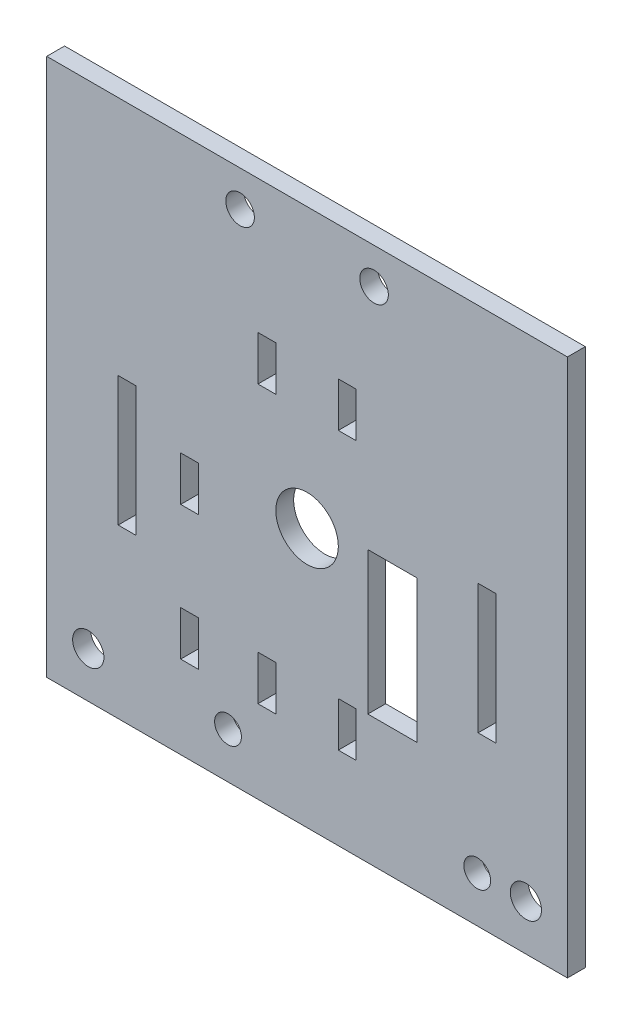
SolidWorks part; units mm, degrees
ref_plane "Front Plane" through (0, 0, 0) normal (0, 0, 1) x (1, 0, 0)
ref_plane "Top Plane" through (0, 0, 0) normal (0, 1, 0) x (1, 0, 0)
ref_plane "Right Plane" through (0, 0, 0) normal (1, 0, 0) x (0, 0, -1)
sketch "Sketch1" plane through (0, 0, 0) normal (0, 0, 1) x (1, 0, 0)
  line L0 (0, 116.93) -> (0, 0) construction
  line L1 (-25.65, 0) -> (25.65, 0)
  line L2 (-26.65, 0) -> (-26.65, 116.93) construction
  line L3 (-26.65, 116.93) -> (26.65, 116.93) construction
  line L4 (26.65, 0) -> (26.65, 116.93) construction
  line L5 (26.65, 128.7773) -> (26.65, 123.7261)
  line L6 (3.5, 106.25) -> (5.5, 106.25)
  line L7 (3.5, 106.25) -> (3.5, 101.25)
  line L8 (3.5, 101.25) -> (5.5, 101.25)
  line L9 (5.5, 106.25) -> (5.5, 101.25)
  line L10 (6.8, 91.35) -> (12.3, 91.35)
  line L11 (6.8, 91.35) -> (6.8, 75.4)
  line L12 (6.8, 75.4) -> (12.3, 75.4)
  line L13 (12.3, 91.35) -> (12.3, 75.4)
  line L14 (19.15, 94.25) -> (21.15, 94.25)
  line L15 (19.15, 94.25) -> (19.15, 79.75)
  line L16 (19.15, 79.75) -> (21.15, 79.75)
  line L17 (21.15, 94.25) -> (21.15, 79.75)
  line L18 (3.5, 75.25) -> (5.5, 75.25)
  line L19 (3.5, 75.25) -> (3.5, 70.25)
  line L20 (3.5, 70.25) -> (5.5, 70.25)
  line L21 (5.5, 75.25) -> (5.5, 70.25)
  line L22 (26.65, 128.7773) -> (-26.65, 128.7773)
  line L23 (-26.65, 99.7544) -> (-26.65, 1)
  line L24 (26.65, 1) -> (26.65, 123.7261)
  line L25 (-5.5, 75.25) -> (-5.5, 70.25)
  line L26 (-3.5, 75.25) -> (-3.5, 70.25)
  line L27 (-3.5, 75.25) -> (-5.5, 75.25)
  line L28 (-3.5, 70.25) -> (-5.5, 70.25)
  line L29 (-19.15, 94.25) -> (-21.15, 94.25)
  line L30 (-19.15, 79.75) -> (-21.15, 79.75)
  line L31 (-21.15, 94.25) -> (-21.15, 79.75)
  line L32 (-19.15, 94.25) -> (-19.15, 79.75)
  line L33 (-3.5, 101.25) -> (-5.5, 101.25)
  line L34 (-3.5, 106.25) -> (-5.5, 106.25)
  line L35 (-3.5, 106.25) -> (-3.5, 101.25)
  line L36 (-5.5, 106.25) -> (-5.5, 101.25)
  line L37 (-21.15, 92.25) -> (-5.8071, 92.25) construction
  line L38 (-12.15, 70.25) -> (-14.15, 70.25)
  line L39 (-12.15, 70.25) -> (-12.15, 75.25)
  line L40 (-12.15, 75.25) -> (-14.15, 75.25)
  line L41 (-14.15, 70.25) -> (-14.15, 75.25)
  line L42 (-14.15, 85.25) -> (-12.15, 85.25)
  line L43 (-14.15, 85.25) -> (-14.15, 90.25)
  line L44 (-14.15, 90.25) -> (-12.15, 90.25)
  line L45 (-12.15, 85.25) -> (-12.15, 90.25)
  line L46 (-21.15, 82.4202) -> (-6.2517, 82.4202) construction
  line L47 (-8.85, 66.1) -> (19.05, 66.1) construction
  line L48 (0, 34.3) -> (-24.05, 34.3) construction
  line L49 (-20, 34.3) -> (-20, 36.05)
  line L50 (-7, 36.05) -> (-20, 36.05)
  line L51 (-7, 36.05) -> (-7, 34.3)
  line L52 (-7, 34.3) -> (-7, 32.55)
  line L53 (-7, 32.55) -> (-20, 32.55)
  line L54 (-20, 32.55) -> (-20, 34.3)
  line L55 (0, 34.3) -> (-13.6195, 57.8897) construction
  line L56 (-5.2321, 39.3622) -> (-15.7321, 57.5487)
  line L57 (-15.7321, 57.5487) -> (-12.2679, 59.5487)
  line L58 (-12.2679, 59.5487) -> (-1.7679, 41.3622)
  line L59 (-1.7679, 41.3622) -> (-5.2321, 39.3622)
  line L60 (-14, 58.5487) -> (-3.5, 40.3622) construction
  line L61 (1.7679, 41.3622) -> (5.2321, 39.3622)
  line L62 (15.7321, 57.5487) -> (12.2679, 59.5487)
  line L63 (12.2679, 59.5487) -> (1.7679, 41.3622)
  line L64 (5.2321, 39.3622) -> (15.7321, 57.5487)
  line L65 (7, 34.3) -> (7, 32.55)
  line L78 (7, 36.05) -> (7, 34.3)
  line L131 (7, 32.55) -> (20, 32.55)
  line L132 (20, 32.55) -> (20, 34.3)
  line L133 (20, 34.3) -> (20, 36.05)
  line L134 (7, 36.05) -> (20, 36.05)
  line L135 (-1.7679, 27.2378) -> (-5.2321, 29.2378)
  line L136 (-15.7321, 11.0513) -> (-12.2679, 9.0513)
  line L137 (-5.2321, 29.2378) -> (-15.7321, 11.0513)
  line L138 (-12.2679, 9.0513) -> (-1.7679, 27.2378)
  line L139 (15.7321, 11.0513) -> (12.2679, 9.0513)
  line L140 (1.7679, 27.2378) -> (5.2321, 29.2378)
  line L141 (5.2321, 29.2378) -> (15.7321, 11.0513)
  line L142 (12.2679, 9.0513) -> (1.7679, 27.2378)
  line L143 (-26.65, 99.7544) -> (-26.65, 128.7773)
  circle A2 centre (0, 90) radius 3.5
  arc A6 (25.65, 0) -> (26.65, 1) centre (25.65, 1) ccw
  arc A7 (-25.65, 0) -> (-26.65, 1) centre (-25.65, 1) cw
  circle A8 centre (19.05, 66.1) radius 1.5
  circle A9 centre (-8.85, 66.1) radius 1.5
  circle A10 centre (-24.05, 15.3) radius 1.5
  circle A11 centre (24.15, 14) radius 1.5
  circle A12 centre (0, 34.3) radius 2.5
  circle A22 centre (0, 34.3) radius 7 construction
  point P35 (26.65, 126.6128)
  point P50 (-26.65, 102.6412)
  point P115 (0, 34.3)
  dimension "D11" = 2
  dimension "D15" = 17
  dimension "D28" = 14
  dimension "D29" = 7
  dimension "D30" = 2.5
  dimension "D49" = 1
  dimension "D50" = 3
  dimension "D51" = 3
  dimension "D52" = 3
  dimension "D53" = 3
  dimension "D31" = 7.6
  dimension "D35" = 66.1
  dimension "D39" = 27.9
  dimension "D40" = 15.2
  dimension "D41" = 5
  dimension "D45" = 14
  dimension "D6" = 26
  dimension "D7" = 5
  dimension "D8" = 2
  dimension "D9" = 5
  dimension "D10" = 10
  dimension "D12" = 9.8298
  dimension "D13" = 2.8298
  dimension "D14" = 5
  dimension "D17" = 53.3
  dimension "D18" = 2
  dimension "D19" = 5.5
  dimension "D20" = 2
  dimension "D21" = 15.3
  dimension "D22" = 14.5
  dimension "D23" = 15.95
  dimension "D24" = 5
  dimension "D25" = 5
  dimension "D26" = 2
  dimension "D27" = 5.5
  dimension "D32" = 6.8
  dimension "D33" = 3.5
  dimension "D34" = 3.5
  dimension "D36" = 90
  dimension "D42" = 14.6
  dimension "D43" = 34.3
  dimension "D44" = 1.75
  dimension "D46" = 10.25
  dimension "D54" = 60
  dimension "D55" = 4
  dimension "D56" = 3.5
  dimension "D57" = 21
  dimension "D58" = 13
extrude "Boss-Extrude1" add sketch "Sketch1" along normal blind 2
sketch "草图1" plane through (0, 0, 0) normal (0, 0, -1) x (-1, 0, 0)
  line L0 (-26.65, 62.9796) -> (26.65, 62.9796)
  line L1 (-26.65, 1) -> (-26.65, 128.7773) construction
  line L2 (26.65, 128.7773) -> (26.65, 1) construction
  line L3 (26.65, 62.9796) -> (26.65, 0)
  line L4 (26.65, 0) -> (-26.65, 0)
  line L5 (-26.65, 0) -> (-26.65, 62.9796)
sketch "草图5" plane through (0, 0, 0) normal (0, 0, -1) x (-1, 0, 0)
  line L0 (-26.65, 62.9796) -> (26.65, 62.9796)
  line L1 (26.65, 62.9796) -> (26.65, 0)
  line L2 (26.65, 0) -> (-26.65, 0)
  line L3 (-26.65, 0) -> (-26.65, 62.9796)
extrude "切除-拉伸1" cut sketch "草图5" against normal blind 10
sketch "草图6" plane through (0, 0, 2) normal (0, 0, 1) x (1, 0, 0)
  line L0 (26.65, 66.1) -> (24.5, 66.1)
  line L1 (-26.65, 66.1) -> (-24.5, 66.1)
  line L2 (-26.65, 128.7773) -> (-26.65, 62.9796) construction
  line L3 (26.65, 62.9796) -> (26.65, 128.7773) construction
  circle A1 centre (-24.5, 66.1) radius 1.75
  circle A2 centre (24.5, 66.1) radius 1.75
  dimension "D1" = 2.15
  dimension "D2" = 2.15
extrude "切除-拉伸2" cut sketch "草图6" against normal blind 10
sketch "草图7" plane through (26.65, 0, 0) normal (1, 0, 0) x (0, 0, -1)
  line L1 (-2, 128.7773) -> (0, 128.7773)
  line L2 (-2, 128.7773) -> (-2, 62.9796)
  line L3 (-2, 62.9796) -> (0, 62.9796)
  line L4 (0, 128.7773) -> (0, 62.9796)
extrude "凸台-拉伸1" add sketch "草图7" along normal blind 2.5
sketch "草图8" plane through (-26.65, 0, 0) normal (-1, 0, 0) x (0, 0, 1)
  line L1 (0, 128.7773) -> (2, 128.7773)
  line L2 (0, 128.7773) -> (0, 62.9796)
  line L3 (0, 62.9796) -> (2, 62.9796)
  line L4 (2, 128.7773) -> (2, 62.9796)
extrude "凸台-拉伸2" add sketch "草图8" along normal blind 2.5
sketch "草图9" plane through (0, 62.9796, 0) normal (0, -1, 0) x (1, 0, 0)
  line L1 (-29.15, 2) -> (29.15, 2)
  line L2 (-29.15, 2) -> (-29.15, 0)
  line L3 (-29.15, 0) -> (29.15, 0)
  line L4 (29.15, 2) -> (29.15, 0)
extrude "凸台-拉伸3" add sketch "草图9" along normal blind 2
sketch "草图10" plane through (0, 0, 2) normal (0, 0, 1) x (1, 0, 0)
  line L0 (29.15, 128.7773) -> (29.15, 60.9796) construction
  line L1 (-29.15, 128.7773) -> (29.15, 128.7773)
  line L2 (-29.15, 128.7773) -> (-29.15, 123.7773)
  line L3 (-29.15, 123.7773) -> (29.15, 123.7773)
  line L4 (29.15, 128.7773) -> (29.15, 123.7773)
  dimension "D1" = 5
extrude "切除-拉伸3" cut sketch "草图10" against normal blind 10 contours L3 L4 L1 L2
sketch "草图13" plane through (0, 0, 2) normal (0, 0, 1) x (1, 0, 0)
  line L0 (29.15, 123.7773) -> (29.15, 60.9796) construction
  line L1 (-29.15, 123.7773) -> (29.15, 123.7773)
  line L2 (-29.15, 123.7773) -> (-29.15, 121.2)
  line L3 (-29.15, 121.2) -> (29.15, 121.2)
  line L4 (29.15, 123.7773) -> (29.15, 121.2)
  dimension "D1" = 2.5773
extrude "切除-拉伸4" cut sketch "草图13" against normal blind 10
sketch "草图14" plane through (0, 0, 2) normal (0, 0, 1) x (1, 0, 0)
  line L0 (-29.15, 121.2) -> (-29.15, 117.2)
  line L1 (-29.15, 60.9796) -> (-29.15, 121.2) construction
  line L2 (-29.15, 117.2) -> (-7.5, 117.2)
  line L3 (29.15, 121.2) -> (29.15, 117.2)
  line L4 (-29.15, 121.2) -> (29.15, 121.2) construction
  line L5 (29.15, 121.2) -> (29.15, 60.9796) construction
  line L6 (29.15, 117.2) -> (7.5, 117.2)
  circle A0 centre (-7.5, 117.2) radius 1.6
  circle A1 centre (7.5, 117.2) radius 1.6
  dimension "D3" = 21.65
  dimension "D1" = 4
  dimension "D2" = 21.65
extrude "切除-拉伸5" cut sketch "草图14" against normal blind 10
